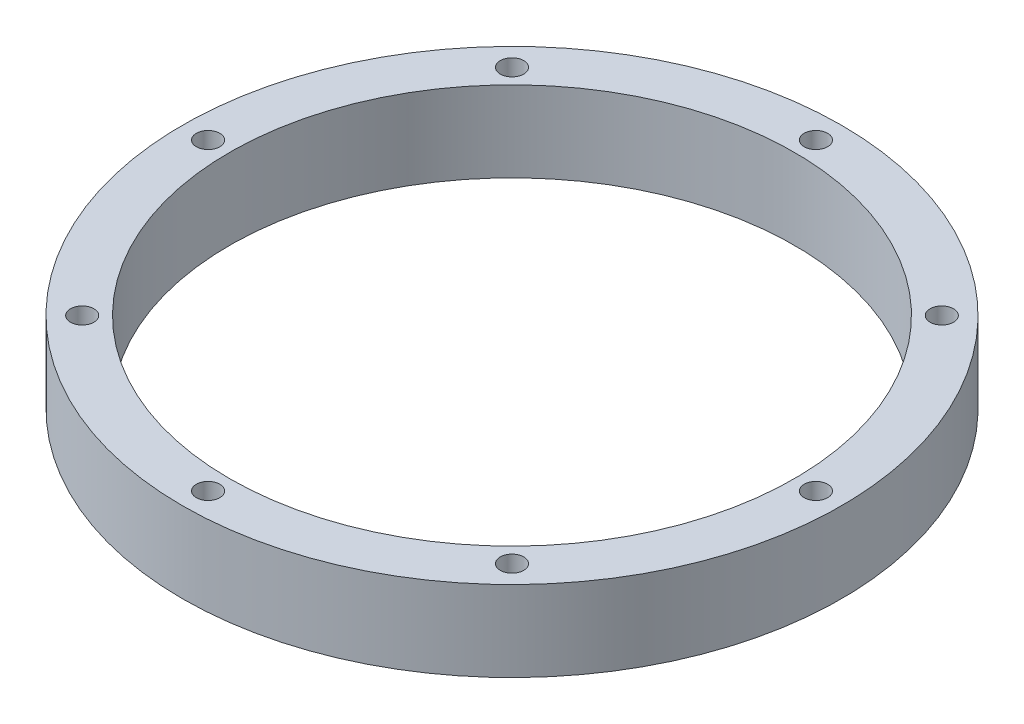
SolidWorks part; units mm, degrees
material "ABS"
ref_plane "Front Plane" through (0, 0, 0) normal (0, 0, 1) x (1, 0, 0)
ref_plane "Top Plane" through (0, 0, 0) normal (0, 1, 0) x (1, 0, 0)
ref_plane "Right Plane" through (0, 0, 0) normal (1, 0, 0) x (0, 0, -1)
sketch "Sketch1" plane through (0, 0, 0) normal (0, 1, 0) x (1, 0, 0)
  line L0 (0, -44.7868) -> (0, 44.7868) construction
  line L1 (-44.2539, 0) -> (44.2539, 0) construction
  circle A0 centre (0, 0) radius 38.575
  circle A1 centre (0, 0) radius 45
  circle A2 centre (0, 41.5) radius 1.6
  circle A3 centre (29.3449, 29.3449) radius 1.6
  circle A4 centre (41.5, 0) radius 1.6
  circle A5 centre (29.3449, -29.3449) radius 1.6
  circle A6 centre (0, -41.5) radius 1.6
  circle A7 centre (-29.3449, -29.3449) radius 1.6
  circle A8 centre (-41.5, 0) radius 1.6
  circle A9 centre (-29.3449, 29.3449) radius 1.6
  point P24 (0, 0)
  dimension "D1" = 77.15
  dimension "D2" = 90
  dimension "D3" = 8
  dimension "D4" = 3.2
  dimension "D5" = 41.5
extrude "Boss-Extrude1" add sketch "Sketch1" along normal blind 11
